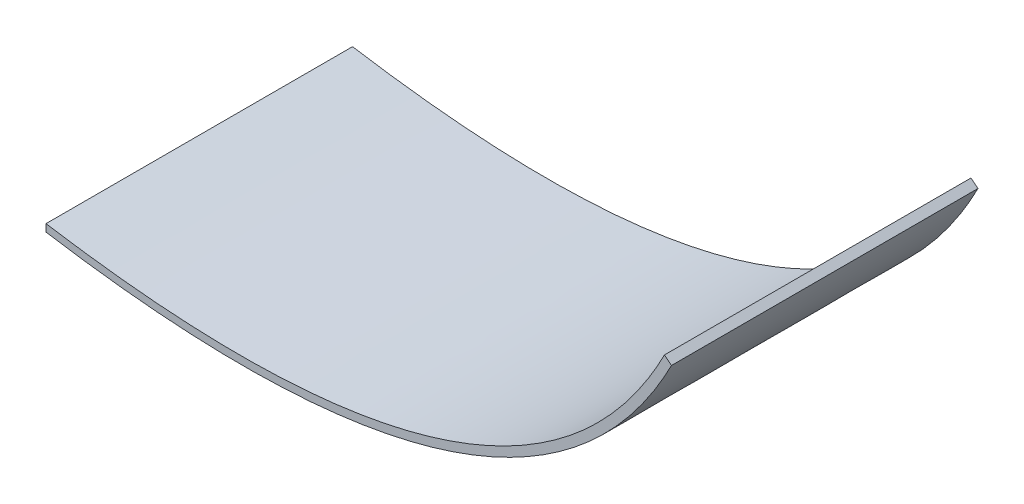
SolidWorks part; units mm, degrees
ref_plane "Front Plane" through (0, 0, 0) normal (0, 0, 1) x (1, 0, 0)
ref_plane "Top Plane" through (0, 0, 0) normal (0, 1, 0) x (1, 0, 0)
ref_plane "Right Plane" through (0, 0, 0) normal (1, 0, 0) x (0, 0, -1)
sketch "Sketch1" plane through (0, 0, 0) normal (0, 0, 1) x (1, 0, 0)
  line L0 (-320.5157, 51.6429) -> (0, 0) construction
  line L1 (0, 0) -> (94.1695, 182.45) construction
  line L2 (-320.5092, 56.5433) -> (-3.7446, 5.5047) construction
  line L3 (-3.7446, 5.5047) -> (89.486, 186.1357) construction
  line L4 (-320.5092, 56.5433) -> (-320.5157, 51.6429)
  line L5 (89.486, 186.1357) -> (94.1695, 182.45)
  line L6 (170.4399, 0) -> (-213.5034, 0) construction
  spline S0 degree 2 poles (-320.5157, 51.6429) (0, 0) (94.1695, 182.45) knots 0 0 0 1 1 1
  spline S1 degree 2 poles (-320.5092, 56.5433) (-3.7446, 5.5047) (89.486, 186.1357) knots 0 0 0 1 1 1
  point P8 (90.625, 185.5432)
  point P9 (-310.8274, 97.4649)
  point P10 (-334.7429, 105.8977)
  point P11 (-334.7429, 109.9805)
  point P12 (0, 0)
  point P13 (-310.1229, 116.9116)
  point P14 (-310.1229, 121.0046)
  point P15 (-320.5092, 51.6429)
  dimension "D1" = 62.7
extrude "Boss-Extrude1" add sketch "Sketch1" along normal blind 203.2 contours S0 L4 S1 L5
